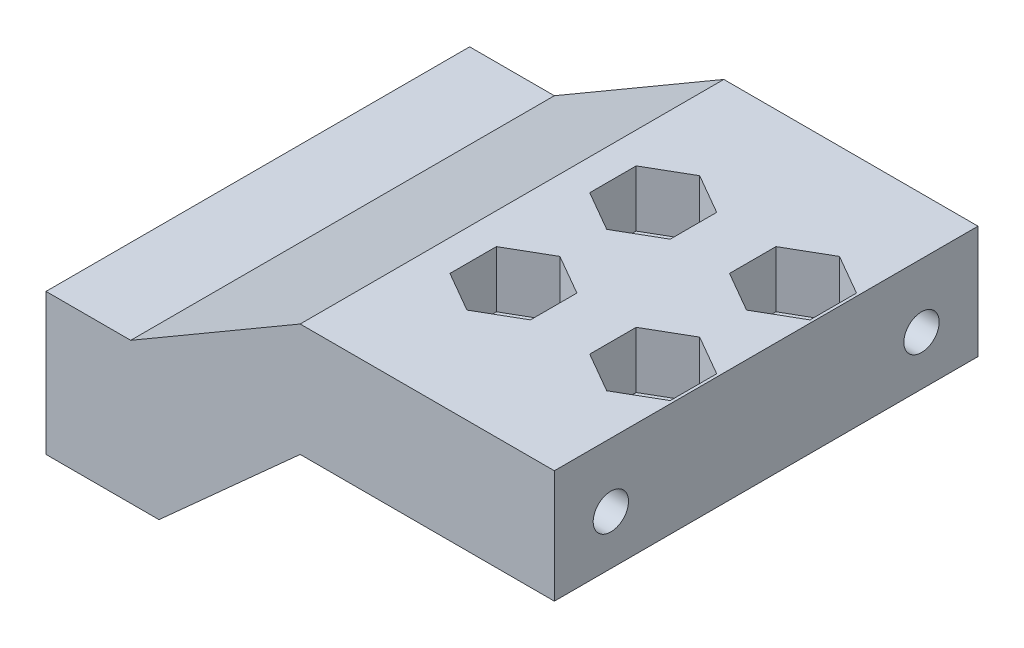
SolidWorks part; units mm, degrees
ref_plane "Спереди" through (0, 0, 0) normal (0, 0, 1) x (1, 0, 0)
ref_plane "Сверху" through (0, 0, 0) normal (0, 1, 0) x (1, 0, 0)
ref_plane "Справа" through (0, 0, 0) normal (1, 0, 0) x (0, 0, -1)
sketch "Эскиз1" plane through (0, 0, 0) normal (0, 1, 0) x (1, 0, 0)
  line L1 (0, 0) -> (41, 0)
  line L2 (0, 0) -> (0, 30)
  line L3 (0, 30) -> (41, 30)
  line L4 (41, 0) -> (41, 30)
  dimension "D1" = 41
  dimension "D2" = 30
extrude "Бобышка-Вытянуть1" add sketch "Эскиз1" along normal blind 10
sketch "Эскиз3" plane through (0, 0, 0) normal (-1, 0, 0) x (0, 0, 1)
  line L0 (-30, 10) -> (0, 10) construction
  line L1 (-30, 10) -> (0, 10)
  line L2 (-30, 10) -> (-30, 0)
  line L3 (-30, 0) -> (0, 0)
  line L4 (0, 10) -> (0, 0)
  line L5 (-30, 0) -> (0, 0) construction
  point P6 (-15, 10)
  point P9 (-15, 0)
  dimension "D1" = 10
  dimension "D2" = 30
extrude "Вырез-Вытянуть2" cut sketch "Эскиз3" against normal blind 3
sketch "Эскиз4" plane through (3, 0, 0) normal (-1, 0, 0) x (0, 0, 1)
  line L0 (-20, 5.4) -> (-8.75, 5.4) construction
  line L1 (0, 10) -> (-30, 10) construction
  line L2 (-20, 4.15) -> (-10, 4.15) construction
  circle A0 centre (-20, 5.4) radius 1.25
  circle A1 centre (-10, 5.4) radius 1.25
  text T0 "отверстия под 2,9 * 9.5  саморез" font "Arial" height 2
  point P5 (-15, 10)
  dimension "D1" = 5
  dimension "D2" = 2.5
  dimension "D3" = 10
  dimension "D4" = 4.6
extrude "Вырез-Вытянуть3" cut sketch "Эскиз4" against normal blind 5
sketch "Эскиз7" plane through (0, 0, -30) normal (0, 0, -1) x (-1, 0, 0)
  line L0 (-39, 10) -> (-39, 17) construction
  line L1 (-39, 17) -> (-21, 17)
  line L2 (-21, 17) -> (-9, 10)
  line L3 (-41, 10) -> (-3, 10) construction
  line L4 (-39, 10) -> (-9, 10)
  line L5 (-39, 17) -> (-39, 10)
  line L6 (-3, 10) -> (-3, 0) construction
  dimension "D1" = 12
  dimension "D2" = 18
  dimension "D3" = 18
  dimension "D4" = 7
extrude "Бобышка-Вытянуть3" add sketch "Эскиз7" against normal blind 30
sketch "Эскиз6" plane through (0, 0, 0) normal (0, -1, 0) x (1, 0, 0)
  line L0 (3, 0) -> (41, 0) construction
  line L1 (41, -30) -> (21, -30)
  line L2 (41, -30) -> (41, 0)
  line L3 (41, 0) -> (21, 0)
  line L4 (21, -30) -> (21, 0)
  dimension "D1" = 20
extrude "Вырез-Вытянуть5" cut sketch "Эскиз6" against normal blind 9
sketch "Эскиз2" plane through (39, 0, 0) normal (1, 0, 0) x (0, 0, -1)
  line L0 (0, 12.5) -> (30, 12.5) construction
  line L1 (0, 17) -> (30, 17) construction
  line L2 (0, 17) -> (0, 10) construction
  circle A0 centre (4, 12.5) radius 1.25
  circle A1 centre (26, 12.5) radius 1.25
  dimension "D1" = 2.5
  dimension "D2" = 2.5
  dimension "D3" = 4.5
  dimension "D4" = 22
  dimension "D5" = 4
extrude "Вырез-Вытянуть1" cut sketch "Эскиз2" against normal blind 4.5
sketch "Эскиз8" plane through (0, 9, 0) normal (0, 1, 0) x (1, 0, 0)
  line L0 (31, 15) -> (37.0104, 21.0104) construction
  line L1 (31, 15) -> (24.9896, 8.9896) construction
  line L2 (21, 0) -> (39, 0) construction
  line L3 (31, 15) -> (42.7004, 15) construction
  line L4 (24.9896, 21.0104) -> (37.0104, 8.9896) construction
  line L6 (21, 0) -> (21, 30) construction
  circle A0 centre (31, 15) radius 7 construction
  circle A1 centre (31, 15) radius 8.5 construction
  circle A2 centre (35.9497, 19.9497) radius 1.5
  circle A3 centre (35.9497, 10.0503) radius 1.5
  circle A4 centre (26.0503, 10.0503) radius 1.5
  circle A5 centre (26.0503, 19.9497) radius 1.5
  point P20 (31, 15)
  dimension "D1" = 14
  dimension "D2" = 17
  dimension "D6" = 4
  dimension "D3" = 10
  dimension "D4" = 15
  dimension "D5" = 45
extrude "Вырез-Вытянуть6" cut sketch "Эскиз8" along normal through all
sketch "Эскиз9" plane through (0, 0, -30) normal (0, 0, -1) x (-1, 0, 0)
  line L0 (-21, 9) -> (-21, 0)
  line L1 (-21, 9) -> (-21, 0) construction
  line L2 (-21, 0) -> (-11, 0)
  line L3 (-21, 0) -> (-3, 0) construction
  line L4 (-11, 0) -> (-21, 9)
  dimension "D1" = 10
extrude "Вырез-Вытянуть7" cut sketch "Эскиз9" against normal through all
sketch "Эскиз10" plane through (0, 17, 0) normal (0, 1, 0) x (1, 0, 0)
  line L1 (26.0503, 23.2406) -> (23.2003, 21.5952)
  line L2 (23.2003, 21.5952) -> (23.2003, 18.3043)
  line L3 (23.2003, 18.3043) -> (26.0503, 16.6589)
  line L4 (26.0503, 16.6589) -> (28.9003, 18.3043)
  line L5 (28.9003, 18.3043) -> (28.9003, 21.5952)
  line L6 (28.9003, 21.5952) -> (26.0503, 23.2406)
  line L7 (35.9497, 23.2406) -> (33.0997, 21.5952)
  line L8 (33.0997, 21.5952) -> (33.0997, 18.3043)
  line L9 (33.0997, 18.3043) -> (35.9497, 16.6589)
  line L10 (35.9497, 16.6589) -> (38.7997, 18.3043)
  line L11 (38.7997, 18.3043) -> (38.7997, 21.5952)
  line L12 (38.7997, 21.5952) -> (35.9497, 23.2406)
  line L13 (35.9497, 13.3411) -> (33.0997, 11.6957)
  line L14 (33.0997, 11.6957) -> (33.0997, 8.4048)
  line L15 (33.0997, 8.4048) -> (35.9497, 6.7594)
  line L16 (35.9497, 6.7594) -> (38.7997, 8.4048)
  line L17 (38.7997, 8.4048) -> (38.7997, 11.6957)
  line L18 (38.7997, 11.6957) -> (35.9497, 13.3411)
  line L19 (26.0503, 13.3411) -> (23.2003, 11.6957)
  line L20 (23.2003, 11.6957) -> (23.2003, 8.4048)
  line L21 (23.2003, 8.4048) -> (26.0503, 6.7594)
  line L22 (26.0503, 6.7594) -> (28.9003, 8.4048)
  line L23 (28.9003, 8.4048) -> (28.9003, 11.6957)
  line L24 (28.9003, 11.6957) -> (26.0503, 13.3411)
  circle A0 centre (26.0503, 19.9497) radius 2.85 construction
  circle A1 centre (35.9497, 19.9497) radius 2.85 construction
  circle A2 centre (35.9497, 10.0503) radius 2.85 construction
  circle A3 centre (26.0503, 10.0503) radius 2.85 construction
  dimension "D1" = 5.7
  dimension "D2" = 5.7
  dimension "D3" = 5.7
  dimension "D4" = 5.7
extrude "Вырез-Вытянуть8" cut sketch "Эскиз10" against normal blind 4
sketch "Эскиз11" plane through (0, 0, -30) normal (0, 0, -1) x (-1, 0, 0)
  line L1 (-39, 10) -> (-43.132, 10)
  line L2 (-39, 10) -> (-39, 6.7442)
  line L3 (-39, 6.7442) -> (-43.132, 6.7442)
  line L4 (-43.132, 10) -> (-43.132, 6.7442)
extrude "Вырез-Вытянуть9" cut sketch "Эскиз11" against normal through all
